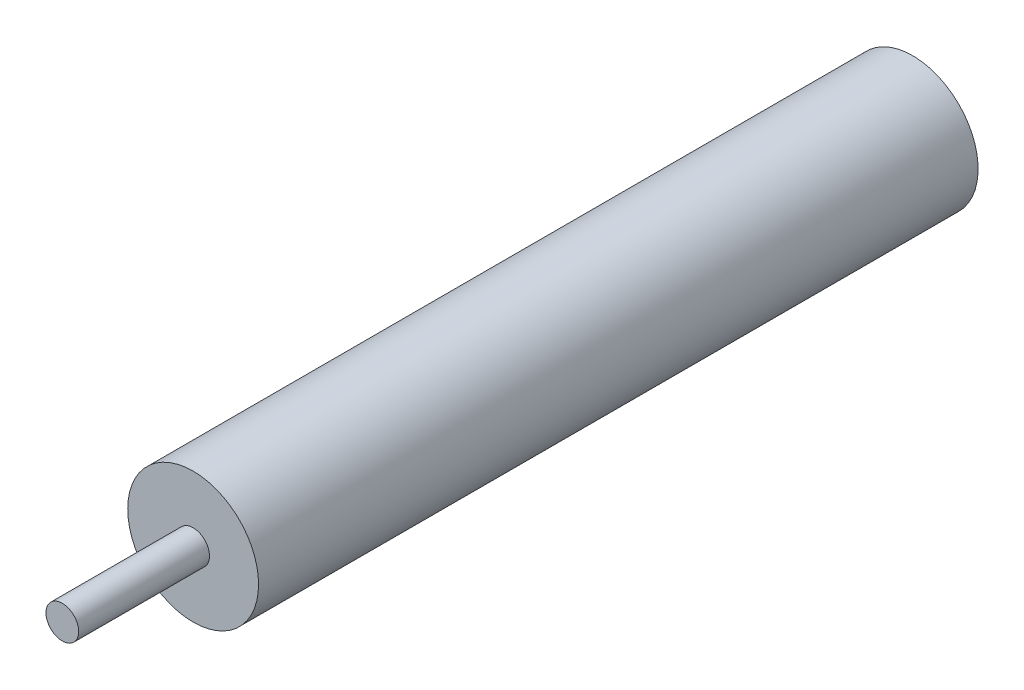
SolidWorks part; units mm, degrees
ref_plane "Front Plane" through (0, 0, 0) normal (0, 0, 1) x (1, 0, 0)
ref_plane "Top Plane" through (0, 0, 0) normal (0, 1, 0) x (1, 0, 0)
ref_plane "Right Plane" through (0, 0, 0) normal (1, 0, 0) x (0, 0, -1)
sketch "Sketch2" plane through (0, 0, 0) normal (0, 0, 1) x (1, 0, 0)
  circle A0 centre (0, 0) radius 10
  dimension "D1" = 20
extrude "Boss-Extrude1" add sketch "Sketch2" along normal blind 95
ref_plane "Plane1" through (0, 0, 0) normal (0, 0, -1) x (-1, 0, 0)
sketch "Sketch3" plane through (0, 0, 0) normal (0, 0, -1) x (-1, 0, 0)
  circle A0 centre (0, 0) radius 10
extrude "Boss-Extrude2" add sketch "Sketch3" along normal blind 15
ref_plane "Plane3" through (0, 0, -15) normal (0, 0, -1) x (-1, 0, 0)
sketch "Sketch5" plane through (0, 0, 95) normal (0, 0, 1) x (1, 0, 0)
  line L0 (10, 0) -> (0, 0) construction
  line L1 (0, 0) -> (0, -10) construction
  line L2 (0, -10) -> (0, 10) construction
  circle A0 centre (0, 0) radius 10 construction
  circle A1 centre (0, 0) radius 2.5
  dimension "D1" = 5
extrude "Boss-Extrude3" add sketch "Sketch5" along normal blind 20
